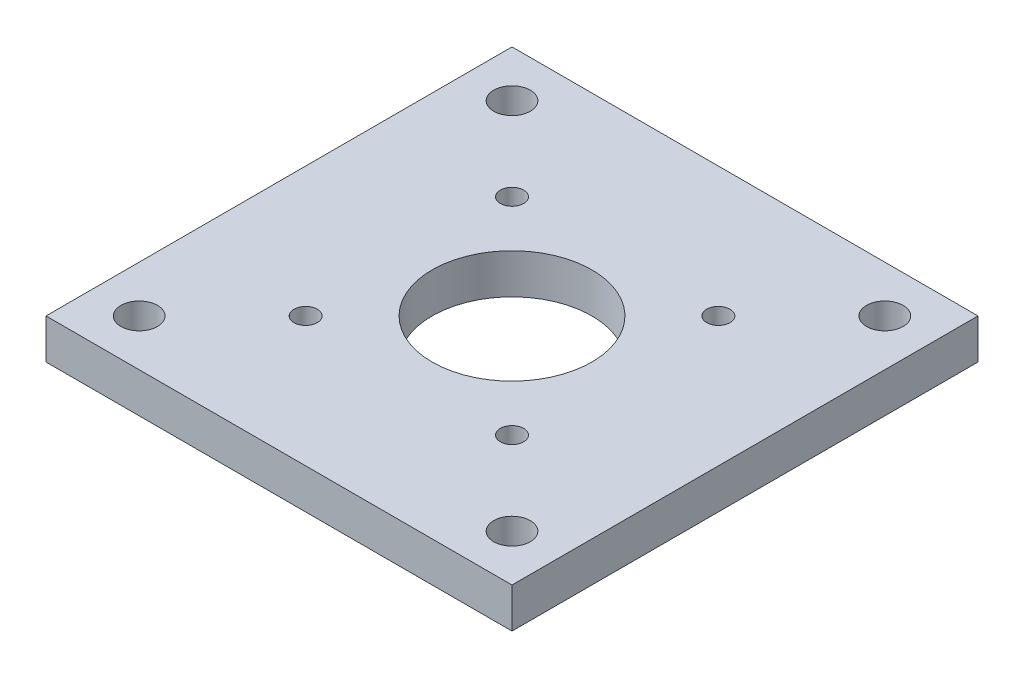
SolidWorks part; units mm, degrees
ref_plane "Front Plane" through (0, 0, 0) normal (0, 0, 1) x (1, 0, 0)
ref_plane "Top Plane" through (0, 0, 0) normal (0, 1, 0) x (1, 0, 0)
ref_plane "Right Plane" through (0, 0, 0) normal (1, 0, 0) x (0, 0, -1)
sketch "Sketch4" plane through (0, 0, 0) normal (0, 1, 0) x (1, 0, 0)
  line L1 (-35, -35) -> (35, -35)
  line L2 (-35, -35) -> (-35, 35)
  line L3 (-35, 35) -> (35, 35)
  line L4 (35, -35) -> (35, 35)
  line L5 (-35, -35) -> (35, 35) construction
  line L6 (-35, 35) -> (35, -35) construction
  circle A0 centre (0, 0) radius 12
  point P0 (0, 0)
  dimension "D3" = 24
  dimension "D1" = 70
  dimension "D2" = 70
extrude "Boss-Extrude2" add sketch "Sketch4" along normal blind 6
sketch "Sketch5" plane through (0, 6, 0) normal (0, 1, 0) x (1, 0, 0)
  line L0 (-35, 0) -> (35, 0) construction
  line L1 (-35, 35) -> (-35, -35) construction
  line L2 (35, -35) -> (35, 35) construction
  line L3 (0, 35) -> (0, -35) construction
  line L4 (35, 35) -> (-35, 35) construction
  line L5 (-35, -35) -> (35, -35) construction
  circle A0 centre (-15.5, 15.5) radius 1.75
  circle A1 centre (15.5, 15.5) radius 1.75
  circle A2 centre (15.5, -15.5) radius 1.75
  circle A3 centre (-15.5, -15.5) radius 1.75
  dimension "D1" = 3.5
  dimension "D2" = 15.5
  dimension "D3" = 15.5
extrude "Cut-Extrude1" cut sketch "Sketch5" against normal through all
sketch "Sketch6" plane through (0, 6, 0) normal (0, 1, 0) x (1, 0, 0)
  line L0 (0, 35) -> (0, -35) construction
  line L1 (35, 35) -> (-35, 35) construction
  line L2 (-35, -35) -> (35, -35) construction
  line L3 (-35, 0) -> (35, 0) construction
  line L4 (-35, 35) -> (-35, -35) construction
  line L5 (35, -35) -> (35, 35) construction
  circle A0 centre (-28, 28) radius 2.75
  circle A2 centre (28, 28) radius 2.75
  circle A3 centre (28, -28) radius 2.75
  circle A4 centre (-28, -28) radius 2.75
  dimension "D1" = 5.5
  dimension "D3" = 28
  dimension "D2" = 28
extrude "Cut-Extrude2" cut sketch "Sketch6" against normal through all
